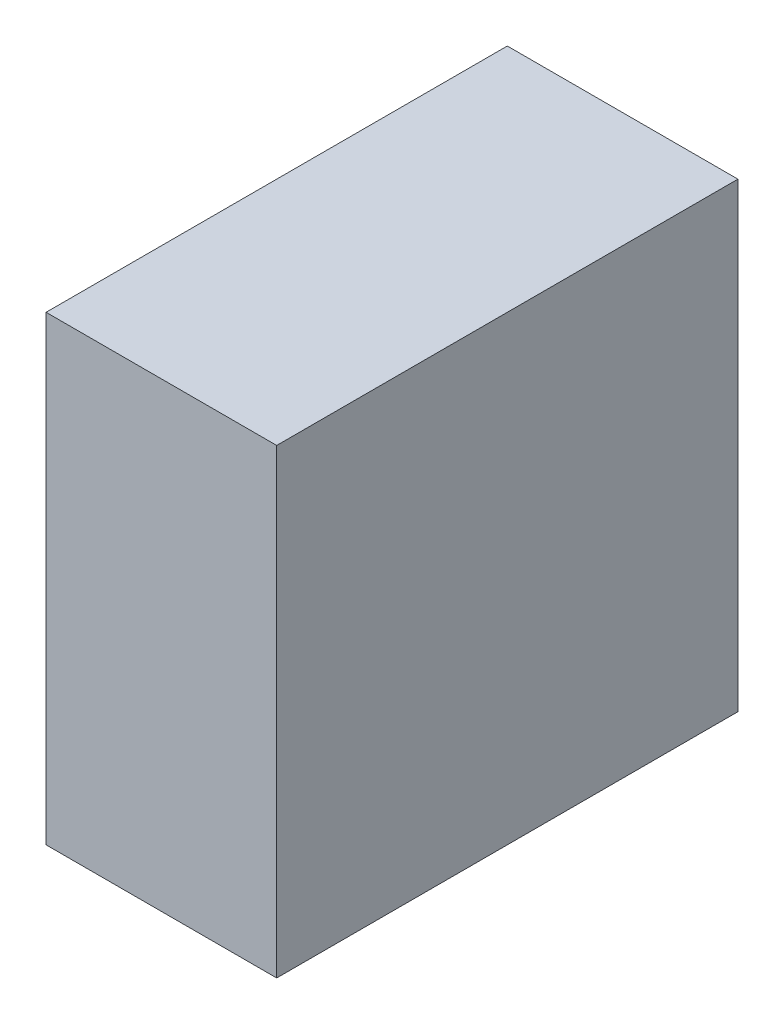
SolidWorks part; units mm, degrees
ref_plane "Front Plane" through (0, 0, 0) normal (0, 0, 1) x (1, 0, 0)
ref_plane "Top Plane" through (0, 0, 0) normal (0, 1, 0) x (1, 0, 0)
ref_plane "Right Plane" through (0, 0, 0) normal (1, 0, 0) x (0, 0, -1)
other "Configuration Table"
sketch "Sketch1" plane through (0, 0, 0) normal (0, 0, 1) x (1, 0, 0)
  line L1 (128, -15) -> (143, -15)
  line L2 (128, -15) -> (128, 15)
  line L3 (128, 15) -> (143, 15)
  line L4 (143, -15) -> (143, 15)
extrude "MTG_enkoder_kapagi_1" add sketch "Sketch1" against normal blind 30 from offset 15 separate body
